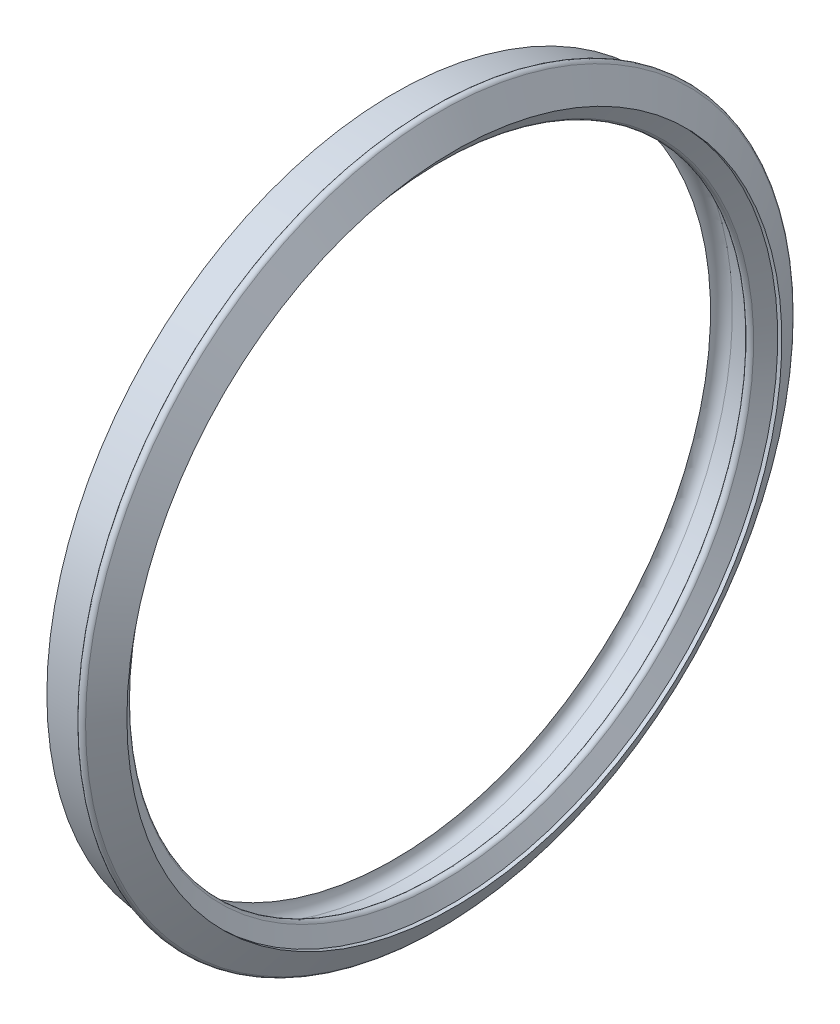
SolidWorks part; units mm, degrees
ref_plane "Спереди" through (0, 0, 0) normal (0, 0, 1) x (1, 0, 0)
ref_plane "Сверху" through (0, 0, 0) normal (0, 1, 0) x (1, 0, 0)
ref_plane "Справа" through (0, 0, 0) normal (1, 0, 0) x (0, 0, -1)
sketch "Эскиз1" plane through (0, 0, 0) normal (0, 0, 1) x (1, 0, 0)
  line L0 (0, 15.9) -> (1.5536, 15.9)
  line L1 (1.5536, 15.9) -> (1.7268, 16.2)
  line L2 (0, 15) -> (1.4226, 15)
  line L3 (1.4226, 15) -> (1.8268, 14.3)
  line L4 (2.1732, 14.3) -> (2.5774, 15)
  line L5 (2.0732, 16.2) -> (2.766, 15)
  line L6 (2.5774, 15) -> (2.766, 15)
  line L7 (0, 15.9) -> (0, 15)
  line L8 (0, 0) -> (22.375, 0) construction
  arc A0 (1.8268, 14.3) -> (2.1732, 14.3) centre (2, 14.4) ccw
  arc A1 (2.0732, 16.2) -> (1.7268, 16.2) centre (1.9, 16.1) ccw
  point P12 (2, 14)
  point P17 (1.9, 16.5)
  dimension "D10" = 0.2
  dimension "D1" = 1
  dimension "D2" = 60
  dimension "D3" = 60
  dimension "D4" = 2
  dimension "D5" = 1.9
  dimension "D6" = 30
  dimension "D7" = 30
  dimension "D8" = 15
  dimension "D9" = 0.9
revolve "Повернуть1" add sketch "Эскиз1" angle 360 about L8
sketch "Эскиз2" plane through (0, 0, 0) normal (0, 0, 1) x (1, 0, 0)
  line L1 (0, 14.5) -> (0, 15)
  line L3 (0, 15) -> (0.5, 15)
  line L4 (0, 0) -> (4.5339, 0) construction
  arc A1 (0, 14.5) -> (0.5, 15) centre (0.5, 14.5) cw
  dimension "D1" = 0.5
revolve "Повернуть2" add sketch "Эскиз2" angle 360 about L4
